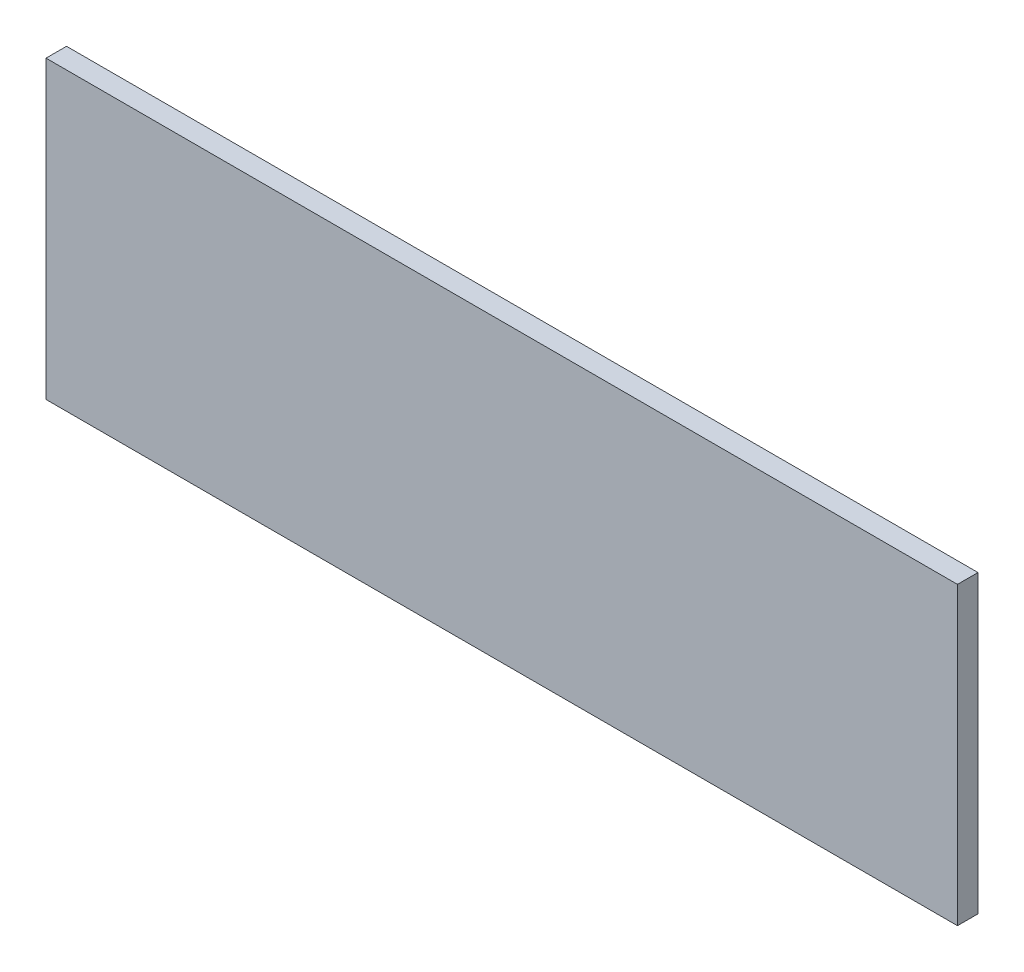
SolidWorks part; units mm, degrees
ref_plane "Front Plane" through (0, 0, 0) normal (0, 0, 1) x (1, 0, 0)
ref_plane "Top Plane" through (0, 0, 0) normal (0, 1, 0) x (1, 0, 0)
ref_plane "Right Plane" through (0, 0, 0) normal (1, 0, 0) x (0, 0, -1)
sketch "Sketch1" plane through (0, 0, 0) normal (0, 0, 1) x (1, 0, 0)
  line L1 (-35.2425, -11.43) -> (35.2425, -11.43)
  line L2 (-35.2425, -11.43) -> (-35.2425, 11.43)
  line L3 (-35.2425, 11.43) -> (35.2425, 11.43)
  line L4 (35.2425, -11.43) -> (35.2425, 11.43)
  line L5 (-35.2425, -11.43) -> (35.2425, 11.43) construction
  line L6 (-35.2425, 11.43) -> (35.2425, -11.43) construction
  point P0 (0, 0)
  dimension "D1" = 22.86
  dimension "D2" = 70.485
extrude "Boss-Extrude1" add sketch "Sketch1" along normal blind 1.5875
